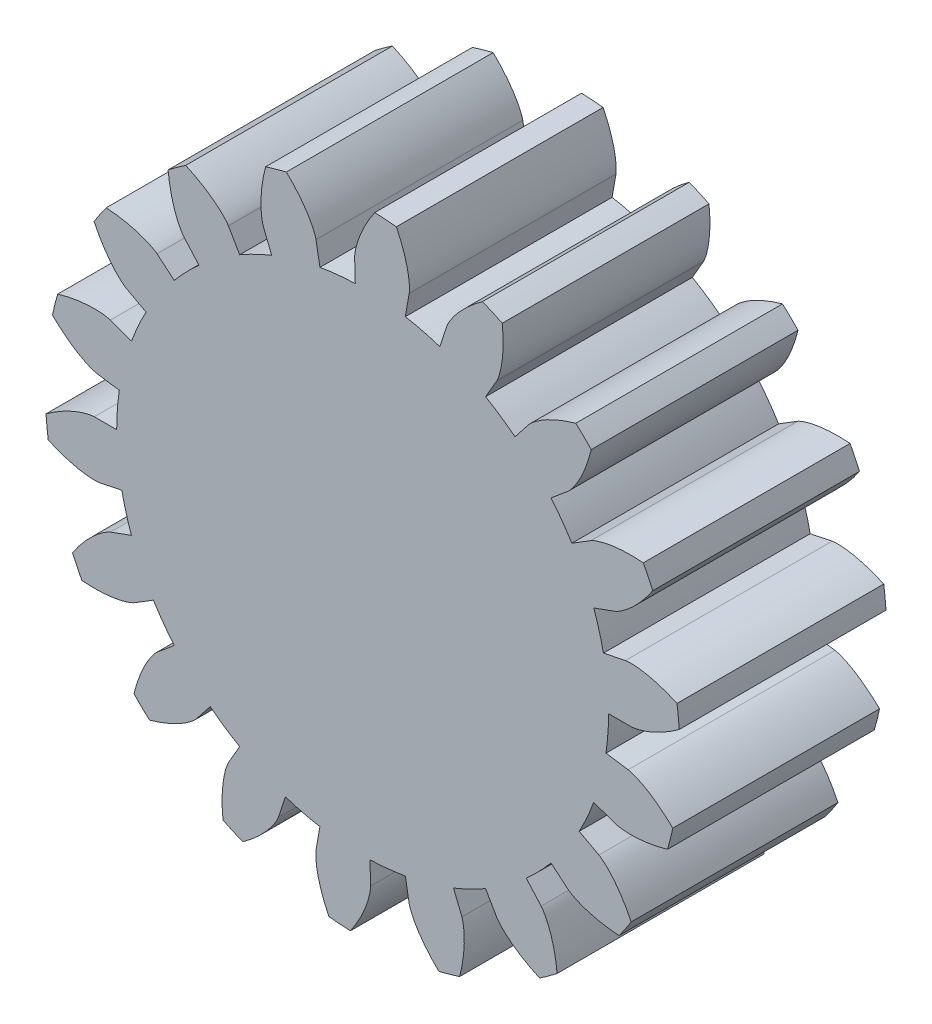
SolidWorks part; units mm, degrees
material "PLA"
ref_plane "Front Plane" through (0, 0, 0) normal (0, 0, 1) x (1, 0, 0)
ref_plane "Top Plane" through (0, 0, 0) normal (0, 1, 0) x (1, 0, 0)
ref_plane "Right Plane" through (0, 0, 0) normal (1, 0, 0) x (0, 0, -1)
sketch "Sketch1" plane through (0, 0, 0) normal (0, 0, 1) x (1, 0, 0)
  circle A0 centre (0, 0) radius 5
  dimension "D1" = 10
extrude "Boss-Extrude1" add sketch "Sketch1" along normal mid plane 3.2579
sketch "Sketch2" plane through (0, 0, 0) normal (0, 0, 1) x (1, 0, 0)
  line L0 (0, 0) -> (4.2286, 0) construction
  line L1 (0, 0) -> (4.4882, -0.3253) construction
  line L2 (0, 0) -> (4.1844, -0.6098) construction
  line L3 (4.2286, 0) -> (3.875, 0)
  line L4 (4.1844, -0.6098) -> (3.8345, -0.5589)
  circle A0 centre (0, 0) radius 4.5 construction
  circle A1 centre (0, 0) radius 4.2286 construction
  circle A2 centre (0, 0) radius 3.875
  circle A3 centre (0, 0) radius 5 construction
  circle A4 centre (0, 0) radius 5
  spline S0 degree 4 poles (4.2286, 0) (4.2327, 0.0001) (4.2403, 0.0005) (4.2528, 0.0016) (4.2774, 0.0047) (4.3051, 0.0095) (4.3362, 0.0161) (4.3694, 0.0245) (4.3978, 0.0325) (4.4259, 0.0411) (4.4538, 0.0504) (4.4875, 0.0624) (4.5277, 0.0778) (4.5743, 0.0973) (4.6267, 0.1213) (4.6796, 0.1476) (4.7313, 0.175) (4.7829, 0.2046) (4.8325, 0.2344) (4.8834, 0.2671) (4.9301, 0.2983) (4.9817, 0.3351) (5.0231, 0.3654) (5.077, 0.4075) (5.1085, 0.4329) (5.1452, 0.4634) (5.1613, 0.4773) (5.1712, 0.4859) knots 0 0 0 0 0 0.015084 0.028532 0.04661 0.092111 0.119476 0.146842 0.174209 0.201575 0.228941 0.256307 0.307035 0.361767 0.4165 0.471232 0.525964 0.580697 0.635429 0.690161 0.744894 0.799626 0.854358 0.909091 0.954545 1 1 1 1 1 construction
  spline S1 degree 4 poles (4.2286, 0) (4.2327, 0.0001) (4.2403, 0.0005) (4.2528, 0.0016) (4.2774, 0.0047) (4.3051, 0.0095) (4.3362, 0.0161) (4.3694, 0.0245) (4.3978, 0.0325) (4.4259, 0.0411) (4.4538, 0.0504) (4.4875, 0.0624) (4.5277, 0.0778) (4.5743, 0.0973) (4.6267, 0.1213) (4.6796, 0.1476) (4.7313, 0.175) (4.7829, 0.2046) (4.8325, 0.2344) (4.8834, 0.2671) (4.9301, 0.2983) (4.9817, 0.3351) (5.0231, 0.3654) (5.0653, 0.3984) (5.0857, 0.4146) (5.0961, 0.423) knots 0 0 0 0 0 0.015084 0.028532 0.04661 0.092111 0.119476 0.146842 0.174209 0.201575 0.228941 0.256307 0.307035 0.361767 0.4165 0.471232 0.525964 0.580697 0.635429 0.690161 0.744894 0.799626 0.854358 0.909091 0.909091 0.909091 0.909091 0.909091
  spline S2 degree 4 poles (4.1844, -0.6098) (4.1884, -0.6105) (4.1959, -0.612) (4.2081, -0.6149) (4.232, -0.6215) (4.2587, -0.6303) (4.2885, -0.6413) (4.3202, -0.6544) (4.3471, -0.6664) (4.3737, -0.679) (4.4, -0.6922) (4.4316, -0.7089) (4.4691, -0.7299) (4.5124, -0.756) (4.5609, -0.7873) (4.6094, -0.8209) (4.6566, -0.8556) (4.7034, -0.8922) (4.7482, -0.9289) (4.7938, -0.9686) (4.8355, -1.0062) (4.8813, -1.0501) (4.9179, -1.0861) (4.9651, -1.1354) (4.9927, -1.1652) (5.0245, -1.2006) (5.0385, -1.2167) (5.0471, -1.2266) knots 0 0 0 0 0 0.015084 0.028532 0.04661 0.092111 0.119476 0.146842 0.174209 0.201575 0.228941 0.256307 0.307035 0.361767 0.4165 0.471232 0.525964 0.580697 0.635429 0.690161 0.744894 0.799626 0.854358 0.909091 0.954545 1 1 1 1 1 construction
  spline S3 degree 4 poles (4.1844, -0.6098) (4.1884, -0.6105) (4.1959, -0.612) (4.2081, -0.6149) (4.232, -0.6215) (4.2587, -0.6303) (4.2885, -0.6413) (4.3202, -0.6544) (4.3471, -0.6664) (4.3737, -0.679) (4.4, -0.6922) (4.4316, -0.7089) (4.4691, -0.7299) (4.5124, -0.756) (4.5609, -0.7873) (4.6094, -0.8209) (4.6566, -0.8556) (4.7034, -0.8922) (4.7482, -0.9289) (4.7938, -0.9686) (4.8355, -1.0062) (4.8813, -1.0501) (4.9179, -1.0861) (4.9549, -1.1247) (4.9728, -1.1438) (4.9818, -1.1536) knots 0 0 0 0 0 0.015084 0.028532 0.04661 0.092111 0.119476 0.146842 0.174209 0.201575 0.228941 0.256307 0.307035 0.361767 0.4165 0.471232 0.525964 0.580697 0.635429 0.690161 0.744894 0.799626 0.854358 0.909091 0.909091 0.909091 0.909091 0.909091
  dimension "D1" = 9
  dimension "D2" = 8.4572
  dimension "D3" = 7.75
  dimension "D4" = 4.146
  dimension "D5" = 4.146
extrude "Cut-Extrude1" cut sketch "Sketch2" against normal through all both and the other way through all contours A2 S3 A4 S1
pattern_circular "CirPattern2" count 18 over 360 about axis through (0, 0, 1.6289) along (0, 0, -1) of "Cut-Extrude1"
sketch "Sketch3" [suppressed] plane through (0, 0, 1.6289) normal (0, 0, 1) x (1, 0, 0)
  circle A0 centre (0, 0) radius 6
  dimension "D1" = 12
equation "\"Np\"= 18"
equation "\"module\"= 0.5"
equation "\"pressure angle\"= 20.0deg"
equation "\"h_a\"= 0.5"
equation "\"h_b\"= 0.625"
equation "\"clr_tip_root\"= 0.125"
equation "\"dp_p\"= 9.0"
equation "\"db_p\"= 8.457233587073176"
equation "\"D1@Sketch1\"= \"dp_p\" + 2*\"h_a\" "
equation "\"fw_p\"= 3.257872803742225"
equation "\"D1@Boss-Extrude1\"=\"fw_p\""
equation "\"D1@Sketch2\"=\"dp_p\""
equation "\"D2@Sketch2\"= \"db_p\""
equation "\"D3@Sketch2\"=\"dp_p\"- 2*\"h_b\""
equation "\"alpha_p\"= 0.8539582918412343"
equation "\"D4@Sketch2\"= 360 / ( 4 * \"Np\" ) - \"alpha_p\""
equation "\"beta_p\"= 8.292083416317531"
equation "\"D5@Sketch2\"= 360 / ( 4 * \"Np\" ) - \"alpha_p\""
equation "\"D1@CirPattern2\"=\"Np\""
equation "\"Nr\"= 63"
equation "\"pressure_angle\"= 20.0deg"
equation "\"h_f\"= 0.625"
equation "\"dp_r\"= 31.5"
equation "\"db_r\"= 29.600317554756117"
equation "\"fw_r\"= 3.257872803742225"
equation "\"alpha_r\"= 0.8539582918412307"
equation "\"beta_r\"= 4.565059440825319"
equation "\"bearing_ID\"= 35"
equation "\"bearing_OD\"= 47"
equation "\"bearing_height\"= 7"
equation "\"clearance_planet\"= 1.5"
equation "\"case_dist\"= 6.5"
equation "\"Motor_case_OD_max\"= 96.5"
equation "\"case_mounting_PCD\"= 89.0"
equation "\"bearing mount thickness\"= 8"
equation "\"case_mounting_hole_dia\"= 3"
equation "\"output_mounting_PCD\"= 55"
equation "\"output_mounting_hole_dia\"= 4"
equation "\"clearance_case_mount_holes_shell_thickness\"= 1"
equation "\"motor_case_OD_base\"= 87.0"
equation "\"sec_carrier_thickness\"= 5"
equation "\"sun_coupler_hub_thickness\"= 4"
equation "\"clearance_sun_coupler_sec_carrier\"= 1.5"
equation "\"clearance_motor_and_case\"= 5"
equation "\"motor_OD\"= 72"
equation "\"Motor_case_thickness\"= 2.5"
equation "\"Motor_case_ID\"= 82"
equation "\"case_mounting_hole_shift\"= 1.0"
equation "\"output_mounting_nut_wrench_size\"= 7"
equation "\"output_mounting_nut_thickness\"= 3.2"
equation "\"case_mounting_hole_allen_socket_dia\"= 5.5"
equation "\"output_mounting_nut_depth\"= 3"
equation "\"case_mounting_bolt_depth\"= 4.5"
equation "\"Ns\"= 27"
equation "\"ring_radial_thickness\"= 5.0"
equation "\"ring_OD\"= 41.5"
equation "\"ring_to_chamfer_clearance\"= 2"
equation "\"Motor_case_OD_base_to_chamfer\"= 5"
equation "\"pattern_offset_from_motor_case_OD_base\"= 3"
equation "\"pattern_bulge_dia\"= 3"
equation "\"pattern_num_bulge\"= 18"
equation "\"pattern_depth\"= 2"
equation "\"motor_height\"= 27"
equation "\"case_mounting_wrench_size\"= 5.5"
equation "\"case_mounting_nut_clearance\"= 2"
equation "\"base_plate_thickness\"= 4"
equation "\"case_mounting_nut_thickness\"= 2.4"
equation "\"case_mounting_surface_height\"= 4"
equation "\"motor_mount_hole_PCD\"= 32"
equation "\"motor_mount_hole_dia\"= 4"
equation "\"motor_mount_hole_num\"= 4"
equation "\"central_hole_offset_from_motor_mount_PCD\"= 5"
equation "\"wire_slot_dist_from_center\"= 26"
equation "\"wire_slot_length\"= 10"
equation "\"wire_slot_radius\"= 2.5"
equation "\"driver_upper_holes_dist_from_center\"= 29"
equation "\"driver_lower_holes_dist_from_center\"= 13"
equation "\"driver_side_holes_dist_from_center\"= 22.5"
equation "\"driver_mount_holes_dia\"= 3"
equation "\"driver_mount_inserts_OD\"= 4.8"
equation "\"driver_mount_thickness\"= 1.5"
equation "\"driver_mount_height\"= 6"
equation "\"air_flow_hole_offset\"= 3"
equation "\"num_planet\"= 3"
equation "\"planet_pin_bolt_dia\"= 5"
equation "\"planet_pin_socket_head_dia\"= 8.5"
equation "\"carrier_PCD\"= 22.5"
equation "\"planet_shaft_dia\"= 8"
equation "\"planet_shaft_step_offset\"= 1"
equation "\"carrier_trapezoidal_support_sun_offset\"= 5"
equation "\"carrier_trapezoidal_support_hole_PCD_offset_bearing_ID\"= 4"
equation "\"carrier_trapezoidal_support_hole_dia\"= 3"
equation "\"carrier_trapezoidal_support_hole_socket_head_dia\"= 5.5"
equation "\"carrier_bearing_step_width\"= 1.5"
equation "\"standard_clearance_1_5mm\"= 1.5"
equation "\"standard_fillet_1_5mm\"= 1.5"
equation "\"sun_shaft_bearing_OD\"= 16"
equation "\"sun_shaft_bearing_width\"= 5"
equation "\"standard_bearing_insertion_chamfer\"= 0.5"
equation "\"carrier_trapezoidal_support_hole_wrench_size\"= 5.5"
equation "\"planet_pin_bolt_wrench_size\"= 8"
equation "\"planet_bearing_OD\"= 12"
equation "\"planet_bearing_width\"= 3.5"
equation "\"planet_bore\"= 10"
equation "\"D1@Sketch3\"=\"planet_bearing_OD\""
